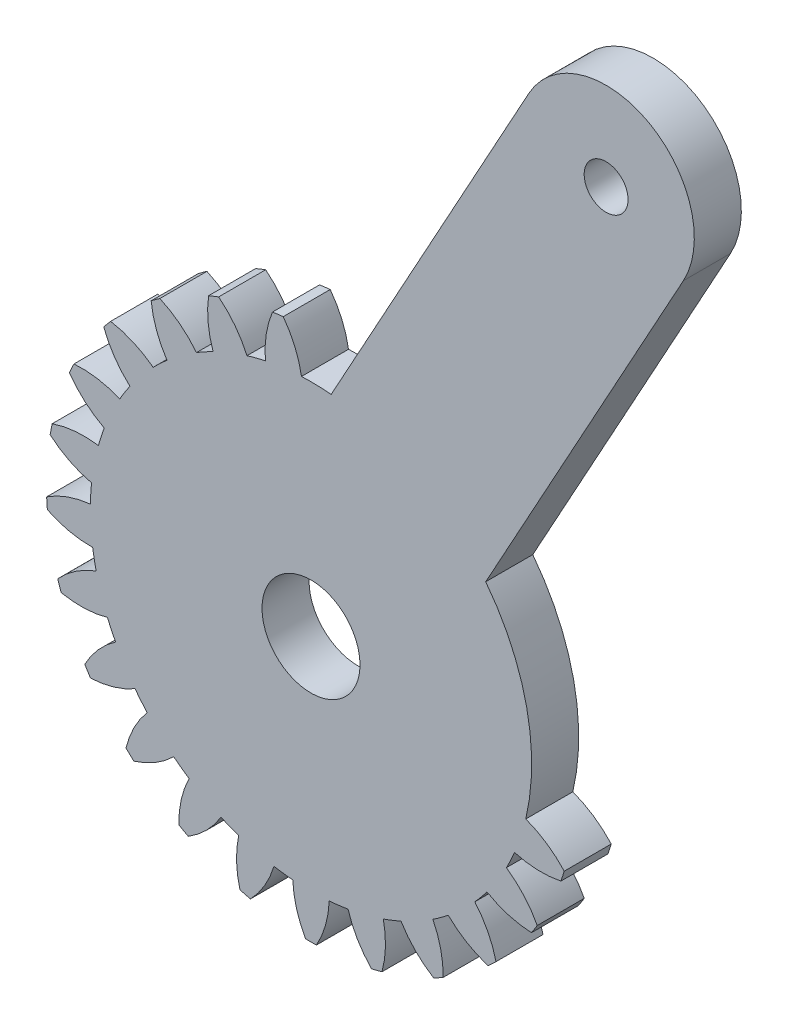
SolidWorks part; units mm, degrees
ref_plane "Front Plane" through (0, 0, 0) normal (0, 0, 1) x (1, 0, 0)
ref_plane "Top Plane" through (0, 0, 0) normal (0, 1, 0) x (1, 0, 0)
ref_plane "Right Plane" through (0, 0, 0) normal (1, 0, 0) x (0, 0, -1)
sketch "Model" plane through (0, 0, 0) normal (0, 0, 1) x (1, 0, 0)
  circle A0 centre (0, 0) radius 3.175
  arc A1 (6.6358, 15.8088) -> (5.9846, 16.0666) centre (0, 0) ccw
  arc A2 (6.343, 12.8165) -> (6.6358, 15.8088) centre (0.3492, 14.9135) ccw
  arc A3 (7.4226, 12.223) -> (6.343, 12.8165) centre (0, 0) ccw
  arc A4 (9.7922, 14.0735) -> (7.4226, 12.223) centre (12.4048, 8.2859) ccw
  arc A5 (10.3588, 13.6619) -> (9.7922, 14.0735) centre (0, 0) ccw
  arc A6 (9.331, 10.8364) -> (10.3588, 13.6619) centre (4.0471, 14.3582) ccw
  arc A7 (10.2291, 9.993) -> (9.331, 10.8364) centre (0, 0) ccw
  arc A8 (12.9845, 11.1962) -> (10.2291, 9.993) centre (14.0757, 4.9407) ccw
  arc A9 (13.4309, 10.6565) -> (12.9845, 11.1962) centre (0, 0) ccw
  arc A10 (11.7328, 8.1754) -> (13.4309, 10.6565) centre (7.4907, 12.9006) ccw
  arc A11 (12.3929, 7.1352) -> (11.7328, 8.1754) centre (0, 0) ccw
  arc A12 (15.3609, 7.6153) -> (12.3929, 7.1352) centre (14.8622, 1.2849) ccw
  arc A13 (15.6591, 6.9816) -> (15.3609, 7.6153) centre (0, 0) ccw
  arc A14 (13.3973, 5.0008) -> (15.6591, 6.9816) centre (10.4636, 10.6324) ccw
  arc A15 (13.778, 3.829) -> (13.3973, 5.0008) centre (0, 0) ccw
  arc A16 (16.7722, 3.556) -> (13.778, 3.829) centre (14.7148, -2.4515) ccw
  arc A17 (16.9034, 2.868) -> (16.7722, 3.556) centre (0, 0) ccw
  arc A18 (14.2201, 1.5119) -> (16.9034, 2.868) centre (12.779, 7.6962) ccw
  arc A19 (14.2974, 0.2823) -> (14.2201, 1.5119) centre (0, 0) ccw
  arc A20 (17.1296, -0.7268) -> (14.2974, 0.2823) centre (13.6429, -6.0339) ccw
  arc A21 (17.0856, -1.4258) -> (17.1296, -0.7268) centre (0, 0) ccw
  arc A22 (14.1493, -2.072) -> (17.0856, -1.4258) centre (14.2915, 4.2764) ccw
  arc A23 (13.9184, -3.2822) -> (14.1493, -2.072) centre (0, 0) ccw
  arc A24 (16.4107, -4.9639) -> (13.9184, -3.2822) centre (11.7137, -9.2372) ccw
  arc A25 (16.1942, -5.63) -> (16.4107, -4.9639) centre (0, 0) ccw
  arc A26 (13.1895, -5.5257) -> (16.1942, -5.63) centre (14.906, 0.5879) ccw
  arc A27 (12.6649, -6.6405) -> (13.1895, -5.5257) centre (0, 0) ccw
  arc A28 (14.6606, -8.8892) -> (12.6649, -6.6405) centre (9.0485, -11.86) ccw
  arc A29 (14.2853, -9.4805) -> (14.6606, -8.8892) centre (0, 0) ccw
  arc A30 (11.4009, -8.6322) -> (14.2853, -9.4805) centre (14.5839, -3.1375) ccw
  arc A31 (10.6156, -9.5815) -> (11.4009, -8.6322) centre (0, 0) ccw
  arc A32 (11.9894, -12.2558) -> (10.6156, -9.5815) centre (5.8147, -13.7377) ccw
  arc A33 (11.4788, -12.7353) -> (11.9894, -12.2558) centre (0, 0) ccw
  arc A34 (8.896, -11.1963) -> (11.4788, -12.7353) centre (13.3455, -6.6658) ccw
  arc A35 (7.8993, -11.9205) -> (8.896, -11.1963) centre (0, 0) ccw
  arc A36 (8.5648, -14.8524) -> (7.8993, -11.9205) centre (2.2156, -14.7522) ccw
  arc A37 (7.9511, -15.1899) -> (8.5648, -14.8524) centre (0, 0) ccw
  arc A38 (5.8321, -13.0569) -> (7.9511, -15.1899) centre (11.2685, -9.7753) ccw
  arc A39 (4.6866, -13.5104) -> (5.8321, -13.0569) centre (0, 0) ccw
  arc A40 (4.6021, -16.5158) -> (4.6866, -13.5104) centre (-1.5227, -14.8397) ccw
  arc A41 (3.9237, -16.69) -> (4.6021, -16.5158) centre (0, 0) ccw
  arc A42 (2.4018, -14.0971) -> (3.9237, -16.69) centre (8.4834, -12.2706) ccw
  arc A43 (1.1795, -14.2515) -> (2.4018, -14.0971) centre (0, 0) ccw
  arc A44 (0.3502, -17.1414) -> (1.1795, -14.2515) centre (-5.1654, -13.9948) ccw
  arc A45 (-0.3502, -17.1414) -> (0.3502, -17.1414) centre (0, 0) ccw
  arc A46 (-1.1795, -14.2515) -> (-0.3502, -17.1414) centre (5.1654, -13.9948) ccw
  arc A47 (-2.4018, -14.0971) -> (-1.1795, -14.2515) centre (0, 0) ccw
  arc A48 (-3.9237, -16.69) -> (-2.4018, -14.0971) centre (-8.4834, -12.2706) ccw
  arc A49 (-4.6021, -16.5158) -> (-3.9237, -16.69) centre (0, 0) ccw
  arc A50 (-4.6866, -13.5104) -> (-4.6021, -16.5158) centre (1.5227, -14.8397) ccw
  arc A51 (-5.8321, -13.0569) -> (-4.6866, -13.5104) centre (0, 0) ccw
  arc A52 (-7.9511, -15.1899) -> (-5.8321, -13.0569) centre (-11.2685, -9.7753) ccw
  arc A53 (-8.5648, -14.8524) -> (-7.9511, -15.1899) centre (0, 0) ccw
  arc A54 (-7.8993, -11.9205) -> (-8.5648, -14.8524) centre (-2.2156, -14.7522) ccw
  arc A55 (-8.896, -11.1963) -> (-7.8993, -11.9205) centre (0, 0) ccw
  arc A56 (-11.4788, -12.7353) -> (-8.896, -11.1963) centre (-13.3455, -6.6658) ccw
  arc A57 (-11.9894, -12.2558) -> (-11.4788, -12.7353) centre (0, 0) ccw
  arc A58 (-10.6156, -9.5815) -> (-11.9894, -12.2558) centre (-5.8147, -13.7377) ccw
  arc A59 (-11.4009, -8.6322) -> (-10.6156, -9.5815) centre (0, 0) ccw
  arc A60 (-14.2853, -9.4805) -> (-11.4009, -8.6322) centre (-14.5839, -3.1375) ccw
  arc A61 (-14.6606, -8.8892) -> (-14.2853, -9.4805) centre (0, 0) ccw
  arc A62 (-12.6649, -6.6405) -> (-14.6606, -8.8892) centre (-9.0485, -11.86) ccw
  arc A63 (-13.1895, -5.5257) -> (-12.6649, -6.6405) centre (0, 0) ccw
  arc A64 (-16.1942, -5.63) -> (-13.1895, -5.5257) centre (-14.906, 0.5879) ccw
  arc A65 (-16.4107, -4.9639) -> (-16.1942, -5.63) centre (0, 0) ccw
  arc A66 (-13.9184, -3.2822) -> (-16.4107, -4.9639) centre (-11.7137, -9.2372) ccw
  arc A67 (-14.1493, -2.072) -> (-13.9184, -3.2822) centre (0, 0) ccw
  arc A68 (-17.0856, -1.4258) -> (-14.1493, -2.072) centre (-14.2915, 4.2764) ccw
  arc A69 (-17.1296, -0.7268) -> (-17.0856, -1.4258) centre (0, 0) ccw
  arc A70 (-14.2974, 0.2823) -> (-17.1296, -0.7268) centre (-13.6429, -6.0339) ccw
  arc A71 (-14.2201, 1.5119) -> (-14.2974, 0.2823) centre (0, 0) ccw
  arc A72 (-16.9034, 2.868) -> (-14.2201, 1.5119) centre (-12.779, 7.6962) ccw
  arc A73 (-16.7722, 3.556) -> (-16.9034, 2.868) centre (0, 0) ccw
  arc A74 (-13.778, 3.829) -> (-16.7722, 3.556) centre (-14.7148, -2.4515) ccw
  arc A75 (-13.3973, 5.0008) -> (-13.778, 3.829) centre (0, 0) ccw
  arc A76 (-15.6591, 6.9816) -> (-13.3973, 5.0008) centre (-10.4636, 10.6324) ccw
  arc A77 (-15.3609, 7.6153) -> (-15.6591, 6.9816) centre (0, 0) ccw
  arc A78 (-12.3929, 7.1352) -> (-15.3609, 7.6153) centre (-14.8622, 1.2849) ccw
  arc A79 (-11.7328, 8.1754) -> (-12.3929, 7.1352) centre (0, 0) ccw
  arc A80 (-13.4309, 10.6565) -> (-11.7328, 8.1754) centre (-7.4907, 12.9006) ccw
  arc A81 (-12.9845, 11.1962) -> (-13.4309, 10.6565) centre (0, 0) ccw
  arc A82 (-10.2291, 9.993) -> (-12.9845, 11.1962) centre (-14.0757, 4.9407) ccw
  arc A83 (-9.331, 10.8364) -> (-10.2291, 9.993) centre (0, 0) ccw
  arc A84 (-10.3588, 13.6619) -> (-9.331, 10.8364) centre (-4.0471, 14.3582) ccw
  arc A85 (-9.7922, 14.0735) -> (-10.3588, 13.6619) centre (0, 0) ccw
  arc A86 (-7.4226, 12.223) -> (-9.7922, 14.0735) centre (-12.4048, 8.2859) ccw
  arc A87 (-6.343, 12.8165) -> (-7.4226, 12.223) centre (0, 0) ccw
  arc A88 (-6.6358, 15.8088) -> (-6.343, 12.8165) centre (-0.3492, 14.9135) ccw
  arc A89 (-5.9846, 16.0666) -> (-6.6358, 15.8088) centre (0, 0) ccw
  arc A90 (-4.1497, 13.6849) -> (-5.9846, 16.0666) centre (-9.9545, 11.1105) ccw
  arc A91 (-2.9563, 13.9913) -> (-4.1497, 13.6849) centre (0, 0) ccw
  arc A92 (-2.4958, 16.9624) -> (-2.9563, 13.9913) centre (3.3706, 14.5318) ccw
  arc A93 (-1.801, 17.0501) -> (-2.4958, 16.9624) centre (0, 0) ccw
  arc A94 (-0.616, 14.2869) -> (-1.801, 17.0501) centre (-6.8786, 13.2371) ccw
  arc A95 (0.616, 14.2869) -> (-0.616, 14.2869) centre (0, 0) ccw
  arc A96 (1.801, 17.0501) -> (0.616, 14.2869) centre (6.8786, 13.2371) ccw
  arc A97 (2.4958, 16.9624) -> (1.801, 17.0501) centre (0, 0) ccw
  arc A98 (2.9563, 13.9913) -> (2.4958, 16.9624) centre (-3.3706, 14.5318) ccw
  arc A99 (4.1497, 13.6849) -> (2.9563, 13.9913) centre (0, 0) ccw
  arc A100 (5.9846, 16.0666) -> (4.1497, 13.6849) centre (9.9545, 11.1105) ccw
  arc A101 (0.616, 14.2869) -> (2.4018, -14.0971) centre (0, 0) cw
extrude "Boss-Extrude1" add sketch "Model" along normal blind 3.048 contours A101 A23 A19 A15 A11 A7 A3 A99 A95 A94 A93 A92 A91 A90 A89 A88 A87 A86 A85 A84 A83 A82 A81 A80 A79 A78 A77 A76 A75 A74 A73 A72 A71 A70 A69 A68 A67 A66 A65 A64 A63 A62 A61 A60 | A40 A101 A42 A41 | A36 A101 A38 A37 | A32 A101 A34 A33 | A28 A101 A30 A29 | A24 A101 A26 A25
sketch "Sketch2" plane through (0, 0, 3.048) normal (0, 0, 1) x (1, 0, 0)
  line L0 (-8.2597, -15.0243) -> (6.8892, 12.5314) construction
  line L1 (1.307, 14.2403) -> (14.1176, 37.5428)
  line L2 (11.3232, 8.7339) -> (24.1338, 32.0363)
  line L3 (14.1176, 37.5428) -> (24.1338, 32.0363) construction
  arc A0 (-8.5648, -14.8524) -> (-7.9511, -15.1899) centre (0, 0) ccw construction
  arc A1 (13.9184, -3.2822) -> (-0.616, 14.2869) centre (0, 0) ccw construction
  circle A2 centre (19.1257, 34.7896) radius 1.4224
  circle A3 centre (19.1257, 34.7896) radius 5.715
  arc A4 (13.9184, -3.2822) -> (-0.616, 14.2869) centre (0, 0) ccw
  dimension "D1" = 2.8448
  dimension "D2" = 11.43
  dimension "D3" = 25.4
extrude "Boss-Extrude2" add sketch "Sketch2" against normal blind 3.048 contours A4 L2 A3 L1 | A3 A2
